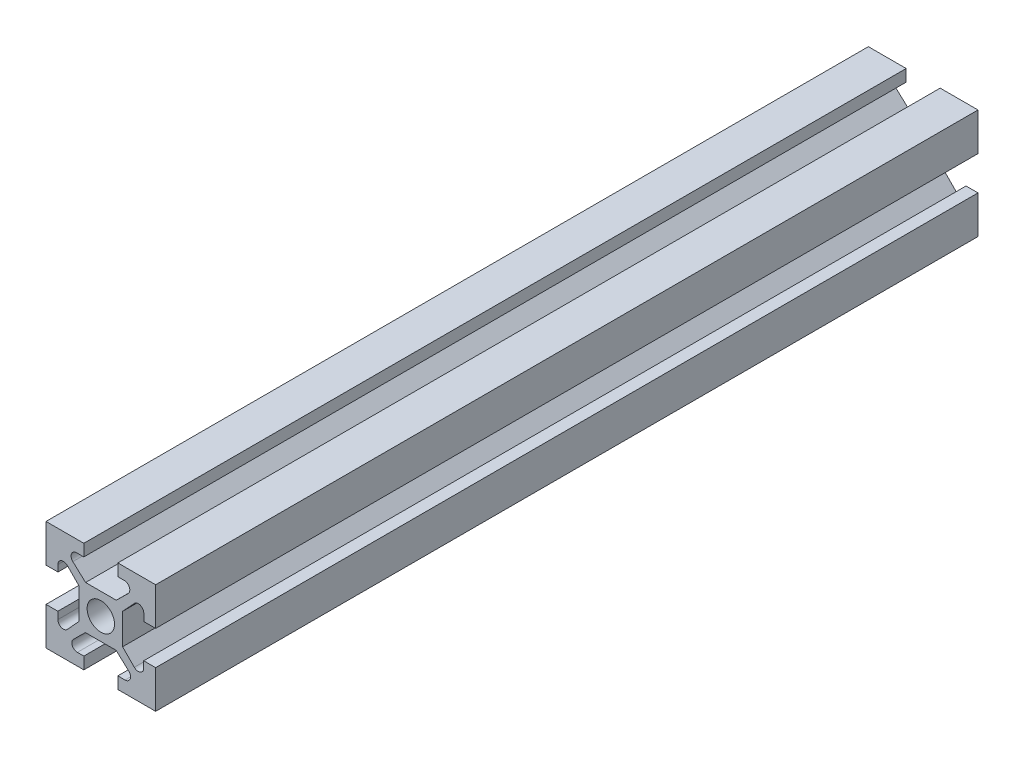
SolidWorks part; units mm, degrees
ref_plane "Front Plane" through (0, 0, 0) normal (0, 0, 1) x (1, 0, 0)
ref_plane "Top Plane" through (0, 0, 0) normal (0, 1, 0) x (1, 0, 0)
ref_plane "Right Plane" through (0, 0, 0) normal (1, 0, 0) x (0, 0, -1)
sketch "Sketch2" plane through (0, 0, 0) normal (0, 0, 1) x (1, 0, 0)
  line L0 (-295.6365, 99.3001) -> (355.6968, 99.3001) construction
  line L1 (53, 177) -> (305, 177) construction
  line L2 (0, 9.9554) -> (0, -10.0446) construction
  line L7 (-10, -10) -> (-3.1, -10)
  line L8 (-10, -10) -> (-10, -3.1)
  line L9 (-10, 10) -> (-3.1, 10)
  line L10 (10, -10) -> (10, -3.1)
  line L11 (-10, -10) -> (10, 10) construction
  line L12 (-10, 10) -> (10, -10) construction
  line L13 (-10, 0) -> (10, 0) construction
  line L14 (-10, 3.1) -> (-7.8186, 3.1)
  line L15 (-7.8186, 3.1) -> (-7.8186, 4.2854)
  line L16 (-6.1072, 4.9882) -> (-3.9647, 2.8197)
  line L17 (-3.9647, 2.8197) -> (-3.9647, 0)
  line L18 (-3.1, 10) -> (-3.1, 7.839)
  line L19 (-3.1, 7.839) -> (-4.4279, 7.839)
  line L20 (-5.1052, 6.1033) -> (-2.7827, 3.9647)
  line L21 (-2.7827, 3.9647) -> (0, 3.9647)
  line L22 (3.1, 10) -> (3.1, 7.8186)
  line L23 (3.1, 7.8186) -> (4.2854, 7.8186)
  line L24 (4.9882, 6.1072) -> (2.8197, 3.9647)
  line L25 (2.8197, 3.9647) -> (0, 3.9647)
  line L26 (6.1033, 5.1052) -> (3.9647, 2.7827)
  line L27 (3.9647, 2.7827) -> (3.9647, 0)
  line L28 (7.839, 3.1) -> (7.839, 4.4279)
  line L29 (10, 3.1) -> (7.839, 3.1)
  line L30 (10, -3.1) -> (7.8186, -3.1)
  line L31 (7.8186, -3.1) -> (7.8186, -4.2854)
  line L32 (6.1072, -4.9882) -> (3.9647, -2.8197)
  line L33 (3.9647, -2.8197) -> (3.9647, 0)
  line L34 (5.1052, -6.1033) -> (2.7827, -3.9647)
  line L35 (2.7827, -3.9647) -> (0, -3.9647)
  line L36 (3.1, -7.839) -> (4.4279, -7.839)
  line L37 (3.1, -10) -> (3.1, -7.839)
  line L38 (-3.1, -10) -> (-3.1, -7.8186)
  line L39 (-3.1, -7.8186) -> (-4.2854, -7.8186)
  line L40 (-4.9882, -6.1072) -> (-2.8197, -3.9647)
  line L41 (-2.8197, -3.9647) -> (0, -3.9647)
  line L42 (-6.1033, -5.1052) -> (-3.9647, -2.7827)
  line L43 (-3.9647, -2.7827) -> (-3.9647, 0)
  line L44 (-7.839, -3.1) -> (-7.839, -4.4279)
  line L45 (-10, -3.1) -> (-7.839, -3.1)
  line L46 (3.1, 10) -> (10, 10)
  line L47 (10, 3.1) -> (10, 10)
  line L48 (3.1, -10) -> (10, -10)
  line L49 (-10, 3.1) -> (-10, 10)
  circle A1 centre (0, 0) radius 2.5
  arc A2 (-4.4279, 7.839) -> (-5.1052, 6.1033) centre (-4.4279, 6.839) ccw
  arc A3 (-7.8186, 4.2854) -> (-6.1072, 4.9882) centre (-6.8186, 4.2854) cw
  arc A4 (4.2854, 7.8186) -> (4.9882, 6.1072) centre (4.2854, 6.8186) cw
  arc A5 (7.839, 4.4279) -> (6.1033, 5.1052) centre (6.839, 4.4279) ccw
  arc A6 (7.8186, -4.2854) -> (6.1072, -4.9882) centre (6.8186, -4.2854) cw
  arc A7 (4.4279, -7.839) -> (5.1052, -6.1033) centre (4.4279, -6.839) ccw
  arc A8 (-4.2854, -7.8186) -> (-4.9882, -6.1072) centre (-4.2854, -6.8186) cw
  arc A9 (-7.839, -4.4279) -> (-6.1033, -5.1052) centre (-6.839, -4.4279) ccw
  dimension "D1" = 3.1
  dimension "D5" = 1
  dimension "D2" = 20
  dimension "D3" = 20
  dimension "D4" = 3.1
  dimension "D6" = 4
extrude "Boss-Extrude1" add sketch "Sketch2" along normal blind 150
